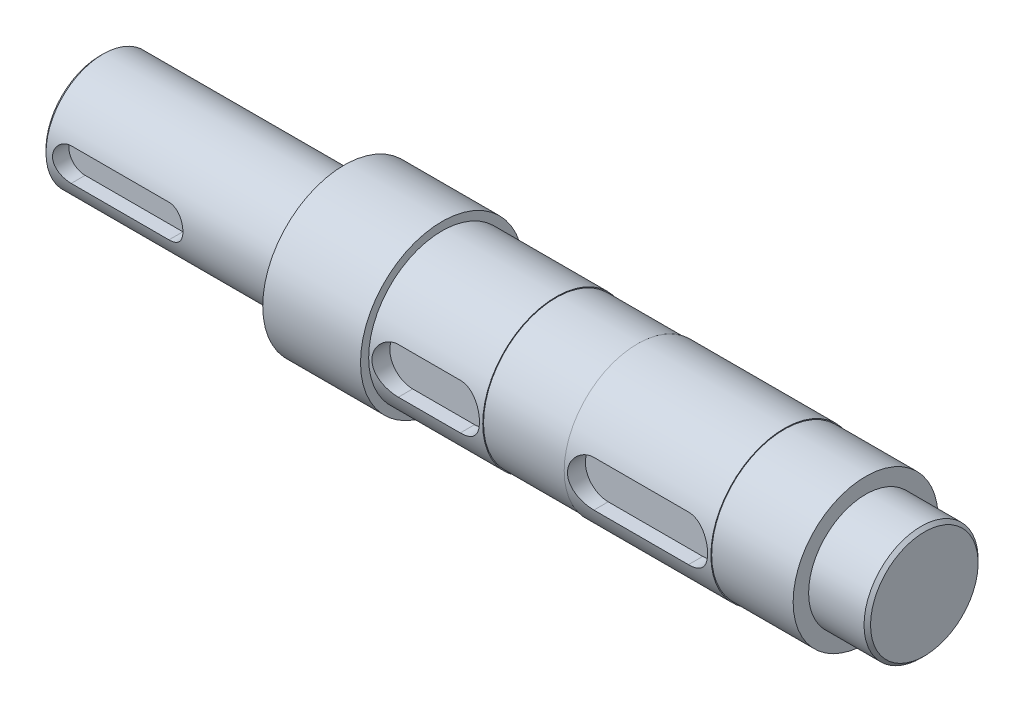
SolidWorks part; units mm, degrees
other "细节项目17"
other "细节项目18"
other "细节项目19"
other "细节项目20"
material "45"
ref_plane "前视基准面" through (0, 0, 0) normal (0, 0, 1) x (1, 0, 0)
ref_plane "上视基准面" through (0, 0, 0) normal (0, 1, 0) x (1, 0, 0)
ref_plane "右视基准面" through (0, 0, 0) normal (1, 0, 0) x (0, 0, -1)
sketch "草图1" plane through (0, 0, 0) normal (0, 0, 1) x (1, 0, 0)
  line L0 (0, 0) -> (50000, 0) construction
  line L1 (0, 0) -> (0, -50000) construction
  line L2 (0, 0) -> (0, 17.5)
  line L3 (0, 17.5) -> (75, 17.5)
  line L4 (75, 17.5) -> (75, 25)
  line L5 (75, 25) -> (105, 25)
  line L6 (235, 22.25) -> (235, 17.5)
  line L7 (235, 17.5) -> (253, 17.5)
  line L8 (253, 17.5) -> (253, 0)
  line L9 (253, 0) -> (0, 0)
  line L10 (105, 25) -> (105, 22.5)
  line L11 (105, 22.5) -> (140, 22.5)
  line L12 (140, 22.5) -> (140, 22.25)
  line L13 (140, 22.25) -> (165, 22.25)
  line L14 (165, 22.25) -> (165, 22.5)
  line L15 (165, 22.5) -> (210, 22.5)
  line L16 (210, 22.5) -> (210, 22.25)
  line L17 (210, 22.25) -> (235, 22.25)
  dimension "D1" = 35
  dimension "D2" = 75
  dimension "D3" = 253
  dimension "D4" = 50
  dimension "D5" = 35
  dimension "D6" = 18
  dimension "D7" = 30
  dimension "D8" = 45
  dimension "D9" = 35
  dimension "D10" = 25
  dimension "D11" = 44.5
  dimension "D12" = 45
  dimension "D14" = 44.5
revolve "旋转1" add sketch "草图1" angle 360 about L0
sketch "草图2" plane through (0, 0, 0) normal (-1, 0, 0) x (0, 0, 1)
  circle A0 centre (0, 0) radius 3
  dimension "D1" = 6
hole_wizard "M6 螺纹孔1" positions "3D草图1" profile "草图3" tap size "M6" standard "Gb"
sketch3d "3D草图1"
  circle A0 centre (0, 0, 0) radius 3 construction
  point P0 (0, 0, 0)
  point P6 (-3, 0, 0)
sketch "草图3" plane through (0, 0, 0) normal (0, 1, 0) x (0, 0, 1)
  line L0 (0, 0) -> (0, 18.5022)
  line L1 (0, 18.5022) -> (2.5, 17)
  line L2 (2.5, 17) -> (2.5, 0)
  line L5 (2.5, 0) -> (0, 0)
  line L10 (0, 18.5022) -> (-2.5, 17) construction
  line L11 (0, -6.35) -> (0, 107.95) construction
  dimension "螺纹孔钻头直径" = 5
  dimension "螺纹孔钻头深度" = 17
  dimension "导头角度" = 118
cosmetic thread "孔螺蚊线1" parameters "D1"=12, "D2"=6
ref_plane "基准面1" through (0, 0, 17) normal (0, 0, 1) x (1, 0, 0)
sketch "草图4" plane through (0, 0, 17) normal (0, 0, 1) x (1, 0, 0)
  line L0 (0, 0) -> (-50000, 0) construction
  line L1 (113, 0) -> (132, 0) construction
  line L2 (113, 7) -> (132, 7)
  line L3 (113, -7) -> (132, -7)
  line L4 (173, 0) -> (202, 0) construction
  line L5 (173, 7) -> (202, 7)
  line L6 (173, -7) -> (202, -7)
  line L7 (105, -22.5) -> (105, 22.5) construction
  line L8 (210, -22.5) -> (210, 22.5) construction
  arc A0 (113, 7) -> (113, -7) centre (113, 0) ccw
  arc A1 (132, -7) -> (132, 7) centre (132, 0) ccw
  arc A2 (173, 7) -> (173, -7) centre (173, 0) ccw
  arc A3 (202, -7) -> (202, 7) centre (202, 0) ccw
  point P5 (122.5, 0)
  point P10 (187.5, 0)
  dimension "D1" = 14
  dimension "D2" = 14
  dimension "D3" = 8
  dimension "D4" = 19
  dimension "D5" = 8
  dimension "D6" = 29
extrude "切除-拉伸1" cut sketch "草图4" along normal blind 10
ref_plane "基准面2" through (0, 0, 12.5) normal (0, 0, 1) x (1, 0, 0)
sketch "草图5" plane through (0, 0, 12.5) normal (0, 0, 1) x (1, 0, 0)
  line L0 (0, 0) -> (-50000, 0) construction
  line L1 (8, 0) -> (38, 0) construction
  line L2 (8, 5) -> (38, 5)
  line L3 (8, -5) -> (38, -5)
  line L4 (0, 17.5) -> (0, -17.5) construction
  arc A0 (8, 5) -> (8, -5) centre (8, 0) ccw
  arc A1 (38, -5) -> (38, 5) centre (38, 0) ccw
  point P5 (23, 0)
  dimension "D1" = 8
  dimension "D2" = 30
  dimension "D3" = 10
extrude "切除-拉伸2" cut sketch "草图5" along normal blind 10
chamfer "倒角1" distance 1 angle 45 2 edges at (253, 0, 17.5) (0, 0, 17.5)
